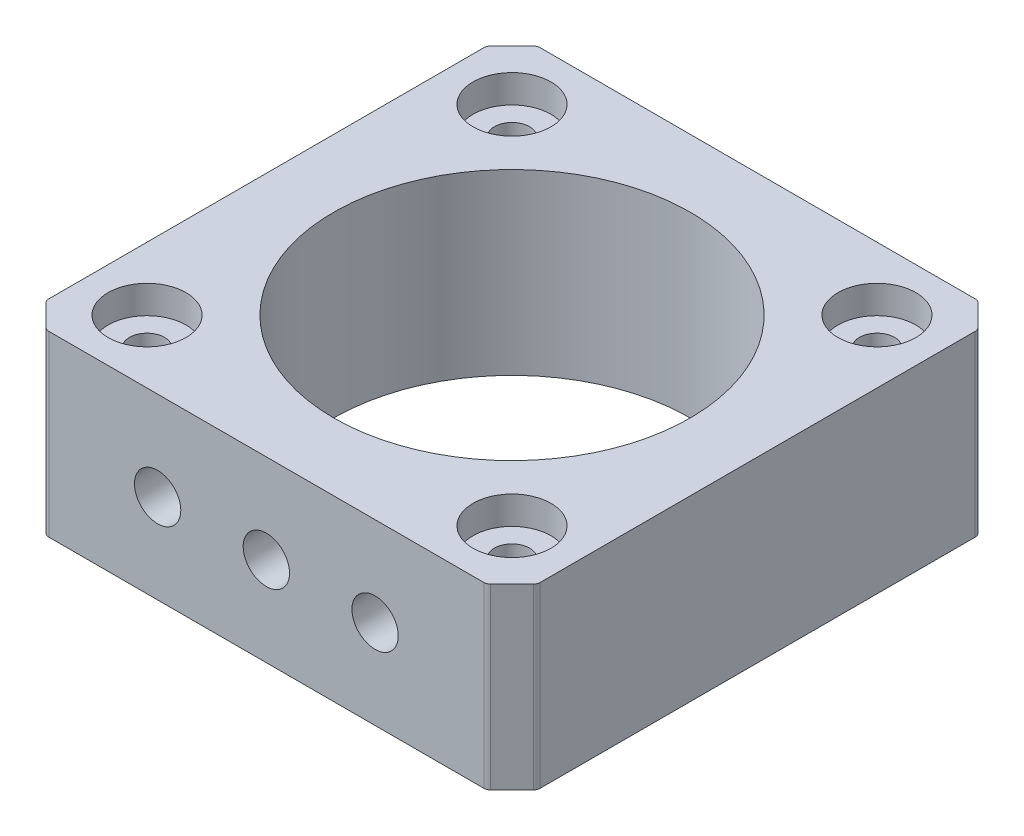
SolidWorks part; units mm, degrees
ref_plane "Front Plane" through (0, 0, 0) normal (0, 0, 1) x (1, 0, 0)
ref_plane "Top Plane" through (0, 0, 0) normal (0, 1, 0) x (1, 0, 0)
ref_plane "Right Plane" through (0, 0, 0) normal (1, 0, 0) x (0, 0, -1)
sketch "Sketch1" plane through (0, 0, 0) normal (0, 1, 0) x (1, 0, 0)
  line L0 (21.6863, 59.206) -> (23.2272, 57.6652)
  line L1 (23.3576, 57.3284) -> (23.3576, 26.3445)
  line L3 (23.2272, 26.0077) -> (21.6863, 24.4669)
  line L6 (21.3495, 24.3364) -> (-9.6343, 24.3364)
  line L7 (-9.9711, 24.4669) -> (-11.512, 26.0077)
  line L8 (-11.6424, 26.3445) -> (-11.6424, 57.3284)
  line L9 (-11.512, 57.6652) -> (-9.9711, 59.206)
  line L10 (-9.6343, 59.3364) -> (21.3495, 59.3364)
  arc A0 (23.2272, 57.6652) -> (23.3576, 57.3284) centre (22.8576, 57.3284) cw
  arc A1 (23.3576, 26.3445) -> (23.2272, 26.0077) centre (22.8576, 26.3445) cw
  arc A2 (21.6863, 24.4669) -> (21.3495, 24.3364) centre (21.3495, 24.8364) cw
  arc A4 (-9.6343, 24.3364) -> (-9.9711, 24.4669) centre (-9.6343, 24.8364) cw
  arc A5 (-11.512, 26.0077) -> (-11.6424, 26.3445) centre (-11.1424, 26.3445) cw
  arc A6 (-11.6424, 57.3284) -> (-11.512, 57.6652) centre (-11.1424, 57.3284) cw
  arc A7 (-9.6343, 59.3364) -> (-9.9711, 59.206) centre (-9.6343, 58.8364) ccw
  arc A8 (21.6863, 59.206) -> (21.3495, 59.3364) centre (21.3495, 58.8364) ccw
  circle A10 centre (5.8576, 41.8364) radius 12.7
  circle A11 centre (18.8576, 54.8364) radius 1.65
  circle A12 centre (18.8576, 28.8364) radius 1.65
  circle A13 centre (-7.1424, 54.8364) radius 1.65
  circle A14 centre (-7.1424, 28.8364) radius 1.65
  point P4 (22.9695, 20.4794)
  dimension "D1" = 25.4
  dimension "D2" = 3.3
  dimension "D3" = 3.3
  dimension "D4" = 3.3
  dimension "D5" = 3.3
extrude "Boss-Extrude1" add sketch "Sketch1" along normal blind 12.7
sketch "Sketch2" plane through (0, 0, -24.3364) normal (0, 0, 1) x (1, 0, 0)
  line L0 (5.8576, 0) -> (5.8576, 12.7) construction
  line L1 (-9.6343, 0) -> (21.3495, 0) construction
  line L2 (-9.6343, 12.7) -> (21.3495, 12.7) construction
  line L3 (-9.6343, 6.35) -> (5.8576, 6.35) construction
  line L4 (-9.6343, 12.7) -> (-9.6343, 0) construction
  line L5 (5.8576, 6.35) -> (21.3495, 6.35) construction
  line L6 (21.3495, 12.7) -> (21.3495, 0) construction
  circle A0 centre (-1.8884, 6.35) radius 1.65
  circle A1 centre (13.6036, 6.35) radius 1.65
  circle A2 centre (5.8576, 6.35) radius 1.65
  dimension "D1" = 3.3
  dimension "D2" = 3.3
  dimension "D3" = 3.3
extrude "Cut-Extrude1" cut sketch "Sketch2" against normal blind 12.7
sketch "Sketch3" plane through (0, 12.7, 0) normal (0, 1, 0) x (1, 0, 0)
  circle A0 centre (-7.1424, 54.8364) radius 2.7749
  circle A1 centre (18.8576, 54.8364) radius 2.775
  circle A2 centre (-7.1424, 28.8364) radius 2.775
  circle A3 centre (18.8576, 28.8364) radius 2.775
extrude "Cut-Extrude3" cut sketch "Sketch3" against normal blind 1.999
sketch "Sketch7" plane through (0, 10.701, 0) normal (0, 1, 0) x (1, 0, 0)
  circle A0 centre (-7.1424, 28.8364) radius 1.65
extrude "Boss-Extrude2" add sketch "Sketch7" against normal through all
sketch "Sketch8" plane through (0, 10.701, 0) normal (0, 1, 0) x (1, 0, 0)
  circle A0 centre (-7.1424, 54.8364) radius 1.65
extrude "Boss-Extrude3" add sketch "Sketch8" against normal through all
sketch "Sketch9" plane through (0, 10.701, 0) normal (0, 1, 0) x (1, 0, 0)
  circle A0 centre (18.8576, 54.8364) radius 1.65
extrude "Boss-Extrude4" add sketch "Sketch9" against normal through all
sketch "Sketch10" plane through (0, 10.701, 0) normal (0, 1, 0) x (1, 0, 0)
  circle A0 centre (18.8576, 28.8364) radius 1.65
extrude "Boss-Extrude5" add sketch "Sketch10" against normal through all
sketch "Sketch11" plane through (0, 10.701, 0) normal (0, 1, 0) x (1, 0, 0)
  circle A0 centre (-7.1424, 54.8364) radius 1.25
  dimension "D1" = 2.5
sketch "Sketch12" plane through (0, 10.701, 0) normal (0, 1, 0) x (1, 0, 0)
  circle A0 centre (18.8576, 54.8364) radius 1.25
  circle A1 centre (-7.1424, 28.8364) radius 1.25
  circle A2 centre (18.8576, 28.8364) radius 1.25
extrude "Cut-Extrude4" cut sketch "Sketch12" against normal blind 12.7
extrude "Cut-Extrude5" cut sketch "Sketch11" against normal blind 12.7 contours A0
